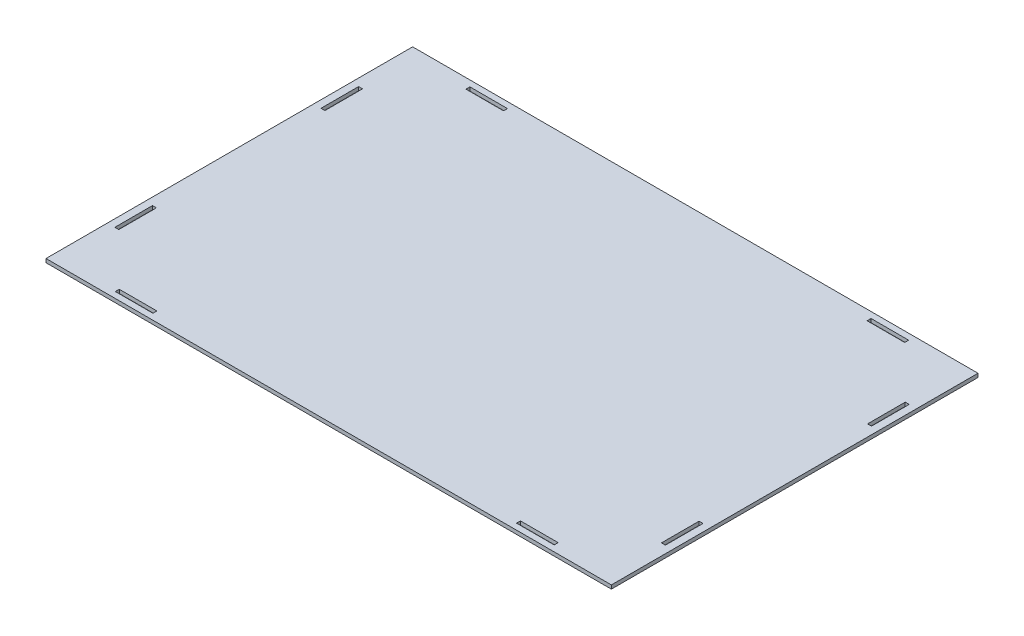
SolidWorks part; units mm, degrees
ref_plane "Alzado" through (0, 0, 0) normal (0, 0, 1) x (1, 0, 0)
ref_plane "Planta" through (0, 0, 0) normal (0, 1, 0) x (1, 0, 0)
ref_plane "Vista lateral" through (0, 0, 0) normal (1, 0, 0) x (0, 0, -1)
sketch "Croquis1" plane through (0, 0, 0) normal (0, 1, 0) x (1, 0, 0)
  line L1 (-227.5, -148.5) -> (227.5, -148.5)
  line L2 (-227.5, -148.5) -> (-227.5, 148.5)
  line L3 (-227.5, 148.5) -> (227.5, 148.5)
  line L4 (227.5, -148.5) -> (227.5, 148.5)
  line L5 (-227.5, -148.5) -> (227.5, 148.5) construction
  line L6 (-227.5, 148.5) -> (227.5, -148.5) construction
  point P0 (0, 0)
  dimension "D1" = 297
  dimension "D2" = 455
extrude "Saliente-Extruir1" add sketch "Croquis1" along normal mid plane 3 contours L1 L4 L3 L2
sketch "Croquis2" plane through (0, 1.5, 0) normal (0, 1, 0) x (1, 0, 0)
  line L0 (-227.5, -148.5) -> (-227.5, 148.5) construction
  line L1 (-177.75, -140.4) -> (-147.25, -140.4)
  line L2 (-177.75, -140.4) -> (-177.75, -143.6)
  line L3 (-177.75, -143.6) -> (-147.25, -143.6)
  line L4 (-147.25, -140.4) -> (-147.25, -143.6)
  line L5 (-177.75, -140.4) -> (-147.25, -143.6) construction
  line L6 (-177.75, -143.6) -> (-147.25, -140.4) construction
  line L7 (-223, -68.25) -> (-219.8, -68.25)
  line L8 (-223, -68.25) -> (-223, -98.75)
  line L9 (-223, -98.75) -> (-219.8, -98.75)
  line L10 (-219.8, -68.25) -> (-219.8, -98.75)
  line L11 (-223, -68.25) -> (-219.8, -98.75) construction
  line L12 (-223, -98.75) -> (-219.8, -68.25) construction
  line L13 (-227.5, -148.5) -> (227.5, -148.5) construction
  line L14 (0, 148.5) -> (0, -154.2743) construction
  line L15 (-227.5, 148.5) -> (227.5, 148.5) construction
  line L16 (223, -98.75) -> (219.8, -68.25) construction
  line L17 (223, -68.25) -> (219.8, -98.75) construction
  line L18 (177.75, -143.6) -> (147.25, -140.4) construction
  line L19 (177.75, -140.4) -> (147.25, -143.6) construction
  line L20 (219.8, -68.25) -> (219.8, -98.75)
  line L21 (223, -98.75) -> (219.8, -98.75)
  line L22 (223, -68.25) -> (223, -98.75)
  line L23 (223, -68.25) -> (219.8, -68.25)
  line L24 (147.25, -140.4) -> (147.25, -143.6)
  line L25 (177.75, -143.6) -> (147.25, -143.6)
  line L26 (177.75, -140.4) -> (177.75, -143.6)
  line L27 (177.75, -140.4) -> (147.25, -140.4)
  line L28 (-1000, 0) -> (49000, 0) construction
  line L29 (177.75, 140.4) -> (147.25, 143.6) construction
  line L30 (177.75, 143.6) -> (147.25, 140.4) construction
  line L31 (223, 68.25) -> (219.8, 98.75) construction
  line L32 (223, 98.75) -> (219.8, 68.25) construction
  line L33 (-223, 98.75) -> (-219.8, 68.25) construction
  line L34 (-223, 68.25) -> (-219.8, 98.75) construction
  line L35 (-177.75, 143.6) -> (-147.25, 140.4) construction
  line L36 (-177.75, 140.4) -> (-147.25, 143.6) construction
  line L37 (177.75, 140.4) -> (147.25, 140.4)
  line L38 (177.75, 140.4) -> (177.75, 143.6)
  line L39 (177.75, 143.6) -> (147.25, 143.6)
  line L40 (147.25, 140.4) -> (147.25, 143.6)
  line L41 (223, 68.25) -> (219.8, 68.25)
  line L42 (223, 68.25) -> (223, 98.75)
  line L43 (223, 98.75) -> (219.8, 98.75)
  line L44 (219.8, 68.25) -> (219.8, 98.75)
  line L45 (-219.8, 68.25) -> (-219.8, 98.75)
  line L46 (-223, 98.75) -> (-219.8, 98.75)
  line L47 (-223, 68.25) -> (-223, 98.75)
  line L48 (-223, 68.25) -> (-219.8, 68.25)
  line L49 (-147.25, 140.4) -> (-147.25, 143.6)
  line L50 (-177.75, 143.6) -> (-147.25, 143.6)
  line L51 (-177.75, 140.4) -> (-177.75, 143.6)
  line L52 (-177.75, 140.4) -> (-147.25, 140.4)
  point P0 (-162.5, -142)
  point P5 (-221.4, -83.5)
  point P28 (221.4, -83.5)
  point P29 (162.5, -142)
  point P48 (162.5, 142)
  point P49 (221.4, 83.5)
  point P50 (-221.4, 83.5)
  point P51 (-162.5, 142)
  dimension "D1" = 49.75
  dimension "D2" = 49.75
  dimension "D3" = 30.5
  dimension "D4" = 30.5
  dimension "D5" = 3.2
  dimension "D6" = 3.2
  dimension "D7" = 4.9
  dimension "D8" = 4.5
extrude "Cortar-Extruir1" cut sketch "Croquis2" against normal mid plane 10
sketch "Croquis3" plane through (-227.5, 0, 0) normal (-1, 0, 0) x (0, 0, 1)
  line L4 (-148.5, -1.5) -> (148.5, -1.5)
  line L5 (148.5, -1.5) -> (148.5, 1.5)
  line L6 (148.5, 1.5) -> (-148.5, 1.5)
  line L7 (-148.5, 1.5) -> (-148.5, -1.5)
  line L8 (-148.5, -1.5) -> (148.5, -1.5)
  line L9 (148.5, -1.5) -> (148.5, 1.5)
  line L10 (148.5, 1.5) -> (-148.5, 1.5)
  line L11 (-148.5, 1.5) -> (-148.5, -1.5)
  dimension "D1" = 0
extrude "Saliente-Extruir2" add sketch "Croquis3" along normal blind 1.5
mirror "Simetría1" about plane through (0, 0, 0) normal (1, 0, 0) of "Saliente-Extruir2"
